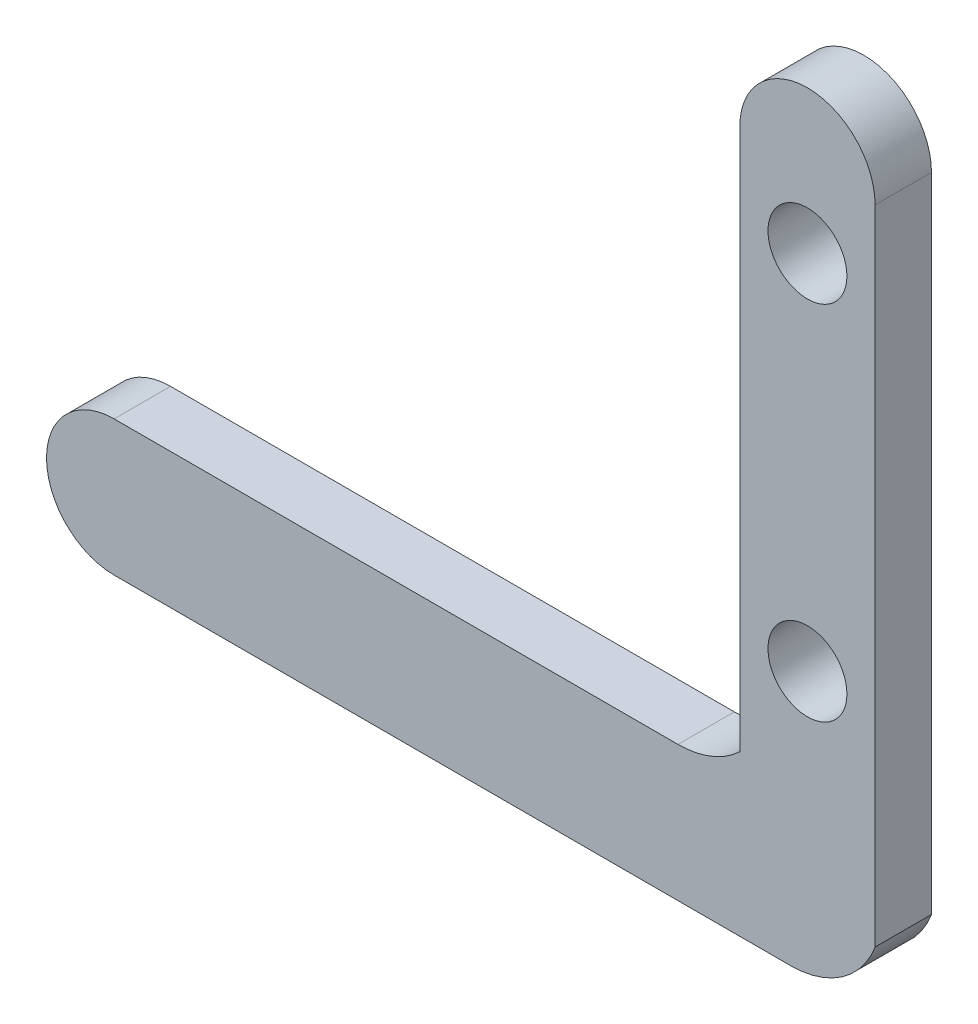
SolidWorks part; units mm, degrees
ref_plane "Plan de face" through (0, 0, 0) normal (0, 0, 1) x (1, 0, 0)
ref_plane "Plan de dessus" through (0, 0, 0) normal (0, 1, 0) x (1, 0, 0)
ref_plane "Plan de droite" through (0, 0, 0) normal (1, 0, 0) x (0, 0, -1)
sketch "Sketch1" plane through (0, 0, 0) normal (0, 0, 1) x (1, 0, 0)
  line L0 (-38.4105, 12) -> (11.5895, 12)
  line L1 (17.0746, 62.1765) -> (17.0746, 14.1765)
  line L2 (29.0746, 62.1765) -> (29.0746, 5.1765)
  line L3 (-38.4105, 0) -> (21.5895, 0)
  arc A0 (11.5895, 12) -> (17.0746, 14.1765) centre (11.5895, 20) ccw
  arc A1 (21.5895, 0) -> (29.0746, 5.1765) centre (21.5895, 8) ccw
  arc A2 (17.0746, 62.1765) -> (29.0746, 62.1765) centre (23.0746, 62.1765) cw
  arc A3 (-38.4105, 12) -> (-38.4105, 0) centre (-38.4105, 6) ccw
  dimension "D3" = 8
  dimension "D4" = 8
  dimension "D1" = 12
  dimension "D2" = 12
  dimension "D5" = 50
  dimension "D6" = 48
  dimension "D7" = 60
  dimension "D8" = 57
extrude "Boss-Extrude1" add sketch "Sketch1" along normal blind 5
sketch "Sketch2" plane through (0, 0, 5) normal (0, 0, 1) x (1, 0, 0)
  line L0 (17.0746, 62.1765) -> (17.0746, 14.1765) construction
  line L1 (29.0746, 5.1765) -> (29.0746, 62.1765) construction
  circle A0 centre (23.0746, 55.451) radius 3.5
  circle A1 centre (23.0746, 23.3599) radius 3.5
  dimension "D3" = 7
  dimension "D4" = 7
  dimension "D1" = 6
  dimension "D2" = 6
extrude "Cut-Extrude1" cut sketch "Sketch2" against normal blind 5
